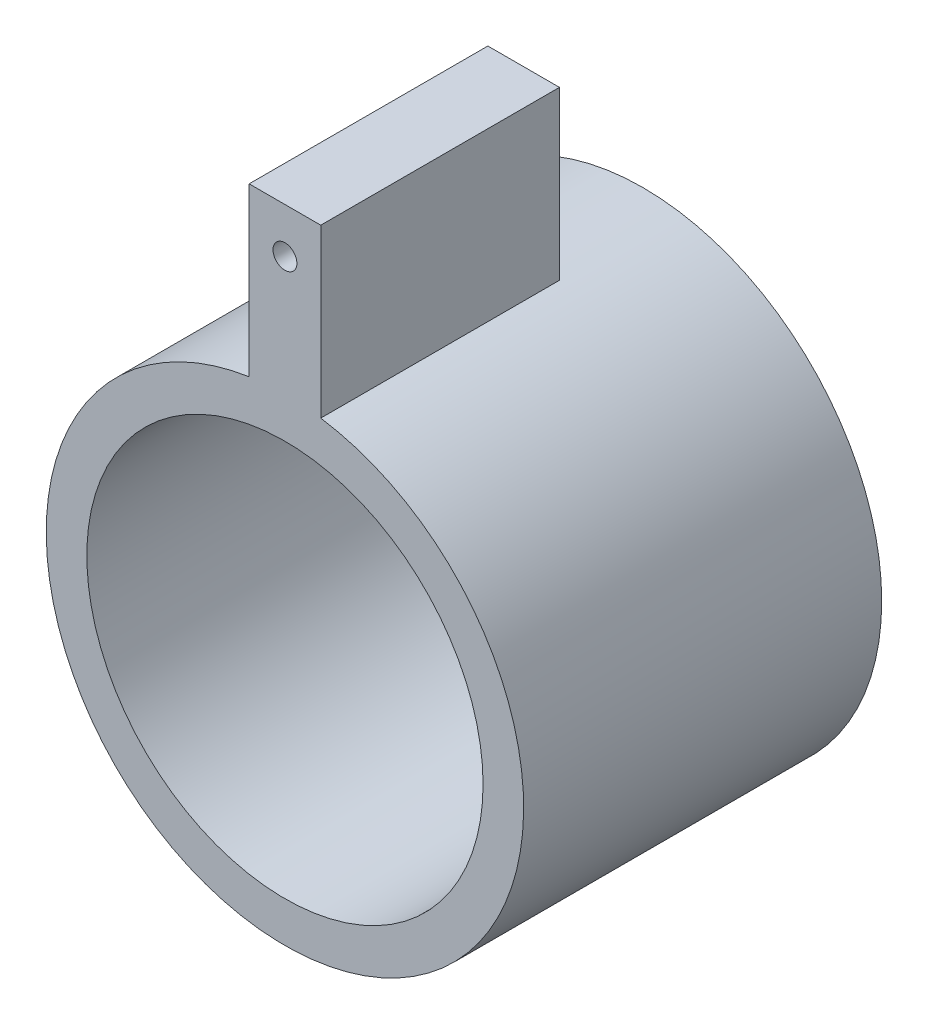
SolidWorks part; units mm, degrees
ref_plane "Front Plane" through (0, 0, 0) normal (0, 0, 1) x (1, 0, 0)
ref_plane "Top Plane" through (0, 0, 0) normal (0, 1, 0) x (1, 0, 0)
ref_plane "Right Plane" through (0, 0, 0) normal (1, 0, 0) x (0, 0, -1)
sketch "Sketch5" plane through (0, 0, 0) normal (0, 0, 1) x (1, 0, 0)
  circle A0 centre (0, 0) radius 8.3
  circle A1 centre (0, 0) radius 10
extrude "Boss-Extrude1" add sketch "Sketch5" along normal blind 15
sketch "Sketch6" plane through (0, 0, 0) normal (0, 0, 1) x (1, 0, 0)
  circle A0 centre (0, 0) radius 10
extrude "Boss-Extrude2" add sketch "Sketch6" along normal blind 2
sketch "Sketch7" plane through (0, 0, 15) normal (0, 0, 1) x (1, 0, 0)
  line L0 (-1.5, 9.8869) -> (-1.5, 16.8869)
  line L1 (1.5, 9.8869) -> (1.5, 16.8869)
  line L2 (-1.5, 16.8869) -> (1.5, 16.8869)
  line L3 (-1.5, 9.8869) -> (1.5, 9.8869)
  circle A0 centre (0, 0) radius 10 construction
  circle A1 centre (0, 15) radius 0.5
  dimension "D1" = 1.5
  dimension "D2" = 1.5
  dimension "D3" = 15
extrude "Boss-Extrude3" add sketch "Sketch7" against normal blind 10
